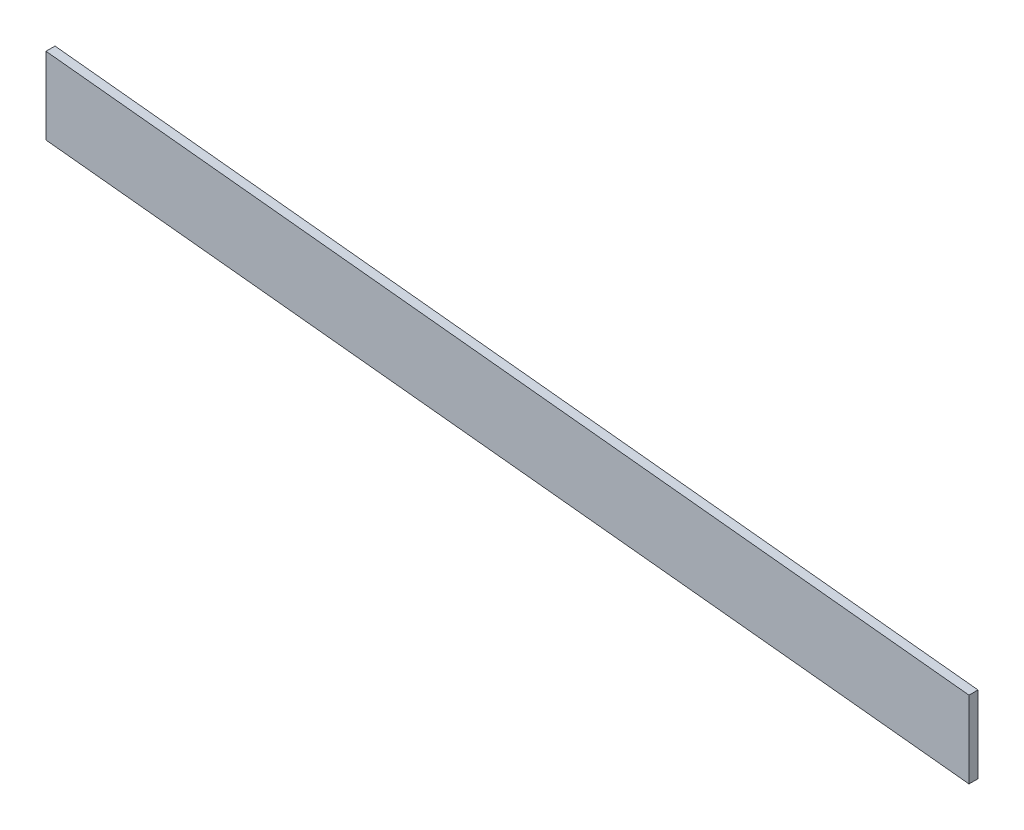
SolidWorks part; units mm, degrees
ref_plane "Front Plane" through (0, 0, 0) normal (0, 0, 1) x (1, 0, 0)
ref_plane "Top Plane" through (0, 0, 0) normal (0, 1, 0) x (1, 0, 0)
ref_plane "Right Plane" through (0, 0, 0) normal (1, 0, 0) x (0, 0, -1)
sketch "Sketch1" plane through (0, 0, 0) normal (0, 0, 1) x (1, 0, 0)
  line L0 (609.6, -114.3) -> (609.6, -12.7)
  line L1 (-609.6, -114.3) -> (609.6, -114.3) construction
  line L2 (-609.6, -114.3) -> (-609.6, 114.3) construction
  line L3 (-609.6, 114.3) -> (609.6, 114.3) construction
  line L4 (609.6, -114.3) -> (609.6, 114.3) construction
  line L5 (-609.6, -114.3) -> (609.6, 114.3) construction
  line L6 (-609.6, 114.3) -> (609.6, -114.3) construction
  line L7 (-609.6, 114.3) -> (-609.6, 12.7)
  line L8 (-609.6, 114.3) -> (609.6, -12.7)
  line L9 (-609.6, 12.7) -> (609.6, -114.3)
  point P0 (0, 0)
  dimension "D1" = 1219.2
  dimension "D2" = 228.6
  dimension "D3" = 101.6
  dimension "D4" = 101.6
extrude "Boss-Extrude1" add sketch "Sketch1" along normal blind 11.9062
